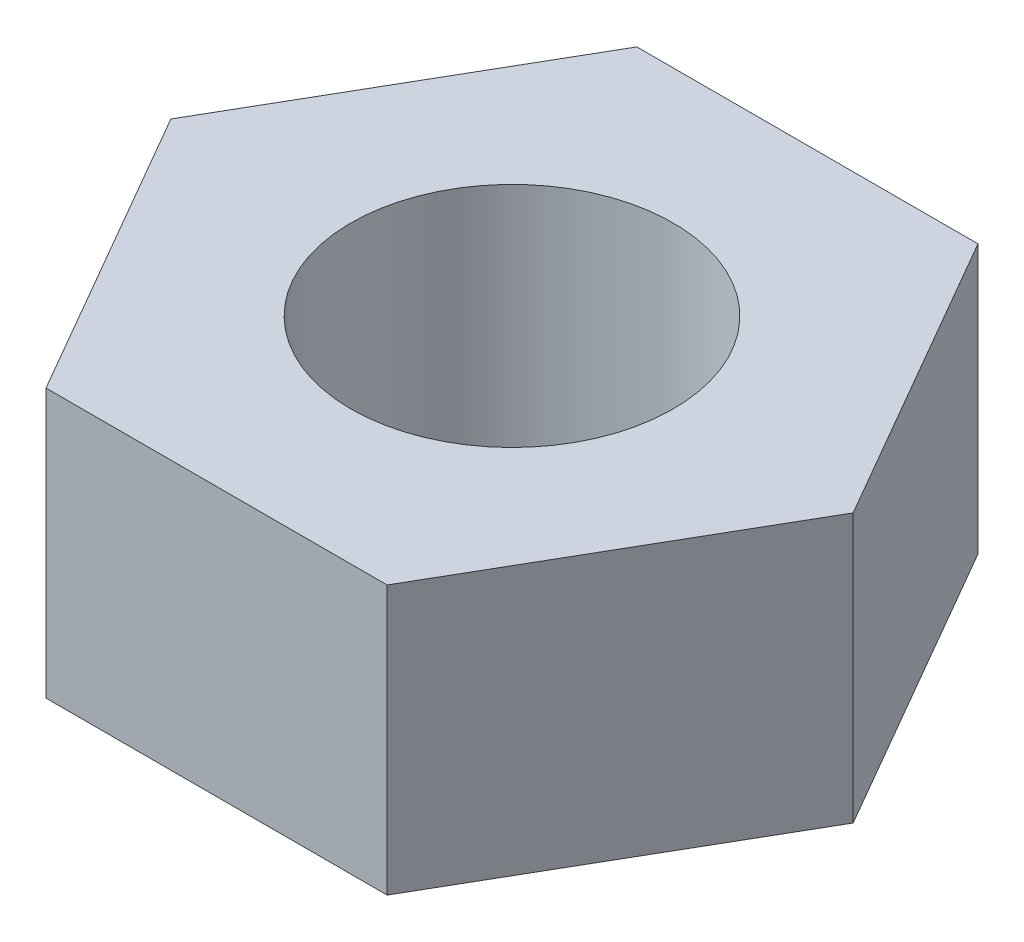
SolidWorks part; units mm, degrees
ref_plane "Front Plane" through (0, 0, 0) normal (0, 0, 1) x (1, 0, 0)
ref_plane "Top Plane" through (0, 0, 0) normal (0, 1, 0) x (1, 0, 0)
ref_plane "Right Plane" through (0, 0, 0) normal (1, 0, 0) x (0, 0, -1)
sketch "Sketch1" plane through (0, 0, 0) normal (0, 1, 0) x (1, 0, 0)
  line L1 (1.5877, 2.75) -> (-1.5877, 2.75)
  line L2 (-1.5877, 2.75) -> (-3.1754, 0)
  line L3 (-3.1754, 0) -> (-1.5877, -2.75)
  line L4 (-1.5877, -2.75) -> (1.5877, -2.75)
  line L5 (1.5877, -2.75) -> (3.1754, 0)
  line L6 (3.1754, 0) -> (1.5877, 2.75)
  circle A0 centre (0, 0) radius 1.5
  circle A1 centre (0, 0) radius 2.75 construction
  point P2 (0, 0)
  dimension "D1" = 5.5
  dimension "D2" = 3
extrude "Boss-Extrude1" add sketch "Sketch1" along normal blind 2.5
